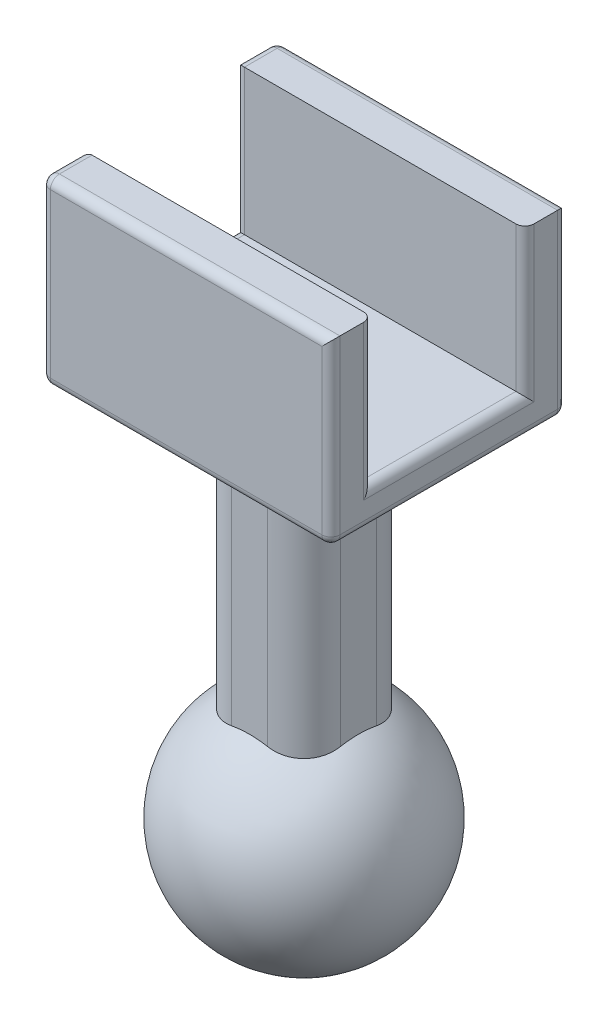
SolidWorks part; units mm, degrees
ref_plane "Front Plane" through (0, 0, 0) normal (0, 0, 1) x (1, 0, 0)
ref_plane "Top Plane" through (0, 0, 0) normal (0, 1, 0) x (1, 0, 0)
ref_plane "Right Plane" through (0, 0, 0) normal (1, 0, 0) x (0, 0, -1)
sketch "Sketch1" plane through (0, 0, 0) normal (0, 0, 1) x (1, 0, 0)
  line L0 (0, -15.875) -> (0, 15.875)
  arc A0 (0, -15.875) -> (0, 15.875) centre (0, 0) ccw
  dimension "D1" = 31.75
revolve "Revolve1" add sketch "Sketch1" angle 360 about L0
sketch "Sketch2" plane through (0, 0, 0) normal (0, 1, 0) x (1, 0, 0)
  line L1 (7.62, -7.62) -> (-7.62, -7.62)
  line L2 (7.62, -7.62) -> (7.62, 7.62)
  line L3 (7.62, 7.62) -> (-7.62, 7.62)
  line L4 (-7.62, -7.62) -> (-7.62, 7.62)
  line L5 (7.62, -7.62) -> (-7.62, 7.62) construction
  line L6 (7.62, 7.62) -> (-7.62, -7.62) construction
  dimension "D2" = 15.24
extrude "Boss-Extrude1" add sketch "Sketch2" along normal blind 50.8
fillet "Fillet1" radius 5.08 4 edges at (-7.62, 31.2285, 7.62) (7.62, 31.2285, 7.62) (-7.62, 31.2285, -7.62) (7.62, 31.2285, -7.62)
sketch "Sketch4" plane through (0, 50.8, 0) normal (0, 1, 0) x (1, 0, 0)
  line L1 (20.2777, -16.51) -> (-20.2777, -16.51)
  line L2 (20.2777, -16.51) -> (20.2777, 16.51)
  line L3 (20.2777, 16.51) -> (-20.2777, 16.51)
  line L4 (-20.2777, -16.51) -> (-20.2777, 16.51)
  line L5 (20.2777, -16.51) -> (-20.2777, 16.51) construction
  line L6 (20.2777, 16.51) -> (-20.2777, -16.51) construction
  point P0 (0, 0)
  dimension "D1" = 40.5554
  dimension "D2" = 33.02
extrude "Boss-Extrude3" add sketch "Sketch4" along normal blind 25.4
sketch "Sketch5" plane through (0, 76.2, 0) normal (0, 1, 0) x (1, 0, 0)
  line L0 (-20.2777, 16.51) -> (-20.2777, -16.51) construction
  line L1 (20.2777, -10.668) -> (-20.2777, -10.668)
  line L2 (20.2777, -10.668) -> (20.2777, 10.668)
  line L3 (20.2777, 10.668) -> (-20.2777, 10.668)
  line L4 (-20.2777, -10.668) -> (-20.2777, 10.668)
  line L5 (20.2777, -10.668) -> (-20.2777, 10.668) construction
  line L6 (20.2777, 10.668) -> (-20.2777, -10.668) construction
  point P0 (0, 0)
  dimension "D1" = 21.336
extrude "Cut-Extrude1" cut sketch "Sketch5" against normal blind 20.32
fillet "Fillet2" radius 1.27 18 edges at (0, 50.8, -16.51) (0, 50.8, 16.51) (20.2777, 66.04, 10.668) (20.2777, 55.88, 0) (20.2777, 66.04, -10.668) (20.2777, 63.5, -16.51) (20.2777, 63.5, 16.51) (20.2777, 50.8, 0) (0, 76.2, -16.51) (-20.2777, 63.5, -16.51) (-20.2777, 76.2, 13.589) (-20.2777, 76.2, -13.589) (-20.2777, 66.04, -10.668) (-20.2777, 55.88, 0) (-20.2777, 66.04, 10.668) (-20.2777, 63.5, 16.51) (-20.2777, 50.8, 0) (0, 76.2, 16.51)
sketch "Sketch3" plane through (0, 50.8, 0) normal (0, 1, 0) x (1, 0, 0)
  circle A0 centre (0, 0) radius 11.43
  dimension "D1" = 22.86
extrude "Boss-Extrude2" add sketch "Sketch3" along normal blind 2.54
